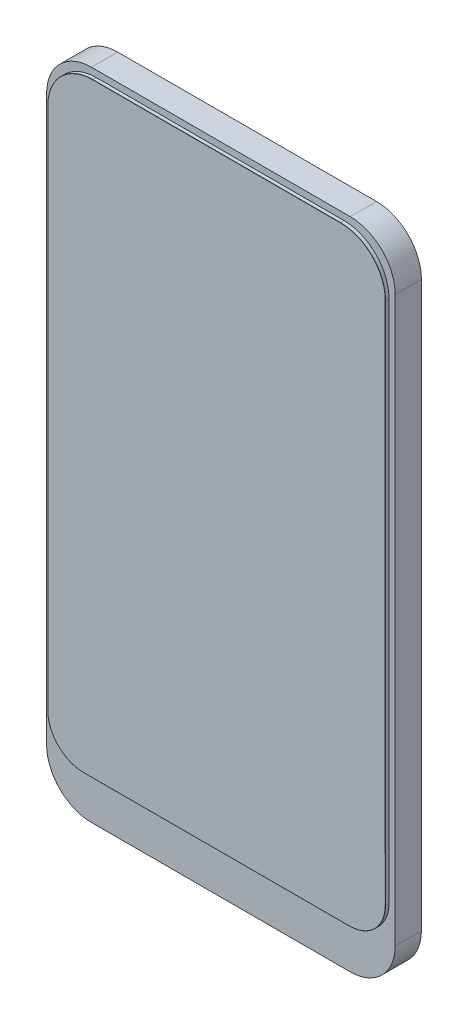
SolidWorks part; units mm, degrees
material "1.4000 (X6Cr13)"
ref_plane "Plan de face" through (0, 0, 0) normal (0, 0, 1) x (1, 0, 0)
ref_plane "Plan de dessus" through (0, 0, 0) normal (0, 1, 0) x (1, 0, 0)
ref_plane "Plan de droite" through (0, 0, 0) normal (1, 0, 0) x (0, 0, -1)
sketch "surfaceutile" plane through (0, 0, 0) normal (0, 0, 1) x (1, 0, 0)
  line L0 (-9.6388, 12.795) -> (9.7512, 12.795) construction
  line L2 (-6.695, -16.175) -> (6.695, -16.175)
  line L3 (-8.695, -14.175) -> (-8.695, 14.175)
  line L4 (-6.695, 16.175) -> (6.695, 16.175)
  line L5 (8.695, -14.175) -> (8.695, 14.175)
  line L6 (-8.695, -16.175) -> (8.695, 16.175) construction
  line L7 (-8.695, 16.175) -> (8.695, -16.175) construction
  arc A0 (-6.695, -16.175) -> (-8.695, -14.175) centre (-6.695, -14.175) cw
  arc A1 (6.695, -16.175) -> (8.695, -14.175) centre (6.695, -14.175) ccw
  arc A2 (6.695, 16.175) -> (8.695, 14.175) centre (6.695, 14.175) cw
  arc A3 (-8.695, 14.175) -> (-6.695, 16.175) centre (-6.695, 14.175) cw
  point P2 (0, 0)
  dimension "D4" = 2
  dimension "D1" = 19.39
  dimension "D2" = 32.35
  dimension "D3" = 17.39
sketch "bord2" plane through (0, 0, 0) normal (0, 0, 1) x (1, 0, 0)
  line L0 (7.395, -19.2062) -> (-31.6755, -19.2062) construction
  line L1 (-7.395, -16.825) -> (7.395, -16.825)
  line L2 (-9.395, -14.825) -> (-9.395, 14.325)
  line L3 (-6.895, 16.825) -> (6.895, 16.825)
  line L4 (9.395, -14.825) -> (9.395, 14.325)
  line L5 (-9.395, -16.825) -> (9.395, 16.825) construction
  line L6 (-9.395, 16.825) -> (9.395, -16.825) construction
  line L7 (-9.6548, 14.4793) -> (-9.6548, -21.2389) construction
  line L8 (7.0562, 17.1884) -> (13.0378, 17.1884) construction
  line L9 (9.7398, -16.5397) -> (9.7398, 19.5607) construction
  arc A0 (7.395, -16.825) -> (9.395, -14.825) centre (7.395, -14.825) ccw
  arc A1 (-7.395, -16.825) -> (-9.395, -14.825) centre (-7.395, -14.825) cw
  arc A2 (6.895, 16.825) -> (9.395, 14.325) centre (6.895, 14.325) cw
  arc A3 (-9.395, 14.325) -> (-6.895, 16.825) centre (-6.895, 14.325) cw
  point P0 (0, 0)
  point P34 (9.7398, 17.1884)
  point P39 (-9.6548, -19.2062)
  dimension "D3" = 2
  dimension "D4" = 2.5
  dimension "D1" = 18.79
  dimension "D2" = 33.65
sketch "bordexterne" plane through (0, 0, 0) normal (0, 0, 1) x (1, 0, 0)
  line L0 (0.0425, -19.2062) -> (0.0425, -5.9083) construction
  line L1 (-7.1548, -19.2062) -> (7.2398, -19.2062)
  line L2 (-9.6548, -16.7062) -> (-9.6548, 14.6884)
  line L3 (-7.1548, 17.1884) -> (7.2398, 17.1884)
  line L4 (9.7398, -16.7062) -> (9.7398, 14.6884)
  line L5 (0.0425, -5.9083) -> (8.695, -5.9083) construction
  line L6 (8.695, -14.175) -> (8.695, 14.175) construction
  line L7 (8.695, -5.9083) -> (-8.695, -5.9083) construction
  line L8 (-8.695, -14.175) -> (-8.695, 14.175) construction
  line L9 (0.0425, -5.9083) -> (-5.6616, -5.9083) construction
  line L10 (-5.6616, -5.9083) -> (5.7412, -5.9083) construction
  line L11 (-5.6616, -5.9083) -> (-5.6616, -3.9085) construction
  line L12 (-5.6616, -3.9085) -> (5.7412, -3.9085) construction
  line L13 (5.7412, -3.9085) -> (5.7412, -5.9083) construction
  line L14 (-4.8276, -32.4986) -> (-4.8276, -3.9085) construction
  line L15 (4.9496, -32.4986) -> (4.9496, -3.9085) construction
  line L16 (-3.7948, -32.4986) -> (-3.7948, -5.5602) construction
  arc A0 (7.2398, -19.2062) -> (9.7398, -16.7062) centre (7.2398, -16.7062) ccw
  arc A1 (-7.1548, -19.2062) -> (-9.6548, -16.7062) centre (-7.1548, -16.7062) cw
  arc A2 (-9.6548, 14.6884) -> (-7.1548, 17.1884) centre (-7.1548, 14.6884) cw
  arc A3 (7.2398, 17.1884) -> (9.7398, 14.6884) centre (7.2398, 14.6884) cw
  point P10 (-9.6548, -19.2062)
  point P15 (9.7398, 17.1884)
  dimension "D1" = 2.5
sketch "connector" plane through (0, 0, 0) normal (0, 0, 1) x (1, 0, 0)
  line L0 (0.0425, -5.9083) -> (8.695, -5.9083) construction
  line L1 (-4.8276, -3.9085) -> (4.9615, -3.9085)
  line L2 (-4.8276, -3.9085) -> (-4.8276, -5.9083)
  line L3 (-4.8276, -5.9083) -> (4.9615, -5.9083)
  line L4 (4.9615, -3.9085) -> (4.9615, -5.9083)
  line L5 (-3.7948, -5.9083) -> (-3.7948, -5.5602)
  line L6 (-3.7948, -32.4986) -> (-3.7948, -5.5602) construction
extrude "Boss.-Extru.1" add sketch "bordexterne" against normal blind 1.46
extrude "Boss.-Extru.2" add sketch "surfaceutile" along normal blind 0.15
extrude "Boss.-Extru.3" add sketch "bord2" along normal blind 0.2
fillet "Congé1" radius 0.01 8 edges at (9.395, -0.25, 0.2) (8.8092, -16.2392, 0.2) (0, -16.825, 0.2) (-8.8092, -16.2392, 0.2) (-9.395, -0.25, 0.2) (-8.6628, 16.0928, 0.2) (0, 16.825, 0.2) (8.6628, 16.0928, 0.2)
sketch "contacts" plane through (0, 0, -1.46) normal (0, 0, -1) x (-1, 0, 0)
  line L1 (-4.9615, -3.9085) -> (4.8276, -3.9085)
  line L2 (-4.9615, -3.9085) -> (-4.9615, -5.9083)
  line L3 (-4.9615, -5.9083) -> (4.8276, -5.9083)
  line L4 (4.8276, -3.9085) -> (4.8276, -5.9083)
extrude "Boss.-Extru.4" add sketch "contacts" along normal blind 0.2
